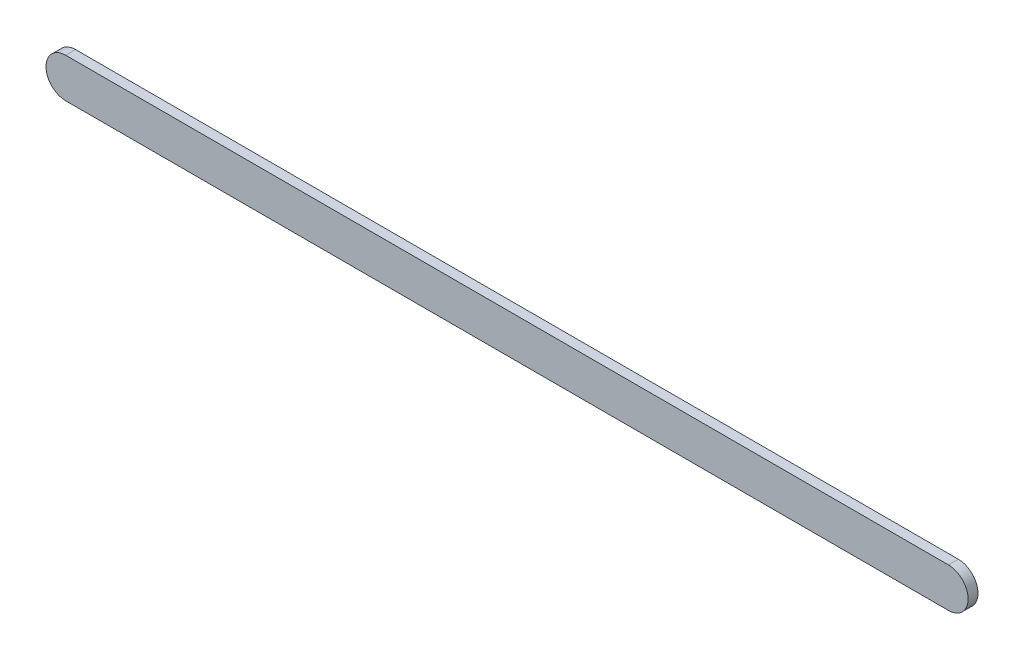
SolidWorks part; units mm, degrees
ref_plane "Front Plane" through (0, 0, 0) normal (0, 0, 1) x (1, 0, 0)
ref_plane "Top Plane" through (0, 0, 0) normal (0, 1, 0) x (1, 0, 0)
ref_plane "Right Plane" through (0, 0, 0) normal (1, 0, 0) x (0, 0, -1)
sketch "Sketch1" plane through (0, 0, 0) normal (0, 0, 1) x (1, 0, 0)
  line L0 (0, 0) -> (-895, 0) construction
  line L1 (0, -20) -> (-895, -20)
  line L2 (0, 20) -> (-895, 20)
  arc A0 (0, -20) -> (0, 20) centre (0, 0) ccw
  arc A1 (-895, 20) -> (-895, -20) centre (-895, 0) ccw
  point P3 (-447.5, 0)
  point P8 (-915, 0)
  dimension "D1" = 20
  dimension "D2" = 915
extrude "Boss-Extrude1" add sketch "Sketch1" along normal mid plane 10
